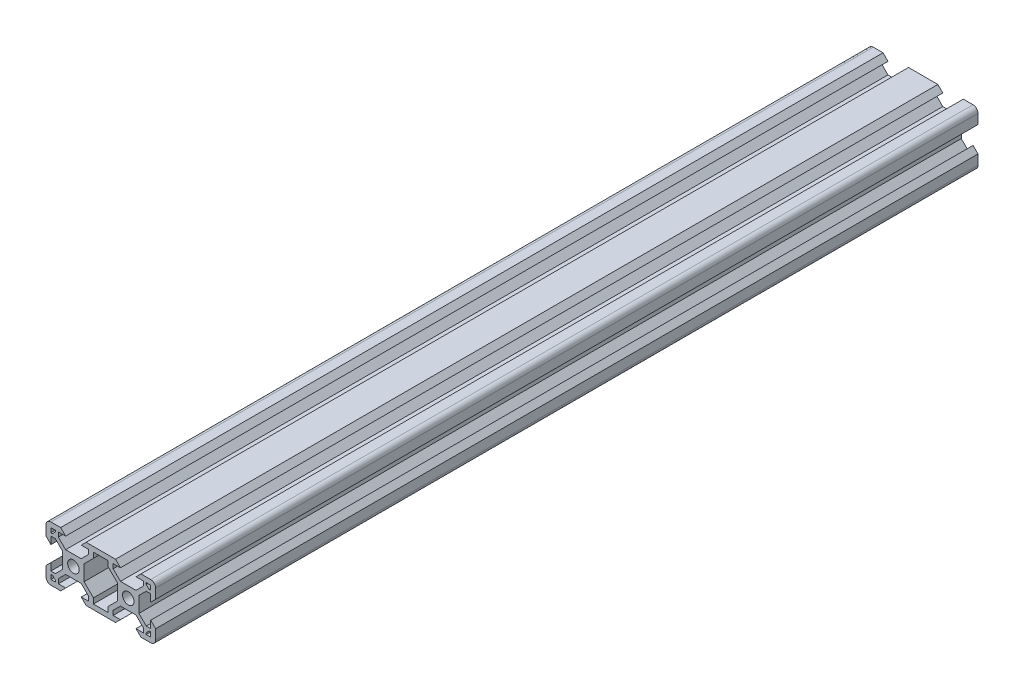
SolidWorks part; units mm, degrees
material "5052-H38, Barre (SS)"
ref_plane "Plan de face" through (0, 0, 0) normal (0, 0, 1) x (1, 0, 0)
ref_plane "Plan de dessus" through (0, 0, 0) normal (0, 1, 0) x (1, 0, 0)
ref_plane "Plan de droite" through (0, 0, 0) normal (1, 0, 0) x (0, 0, -1)
sketch "Esquisse1" plane through (0, 0, 0) normal (0, 0, 1) x (1, 0, 0)
  line L0 (0, 0) -> (0, 10) construction
  line L1 (0, 0) -> (-20, 0) construction
  line L2 (-10, 0) -> (-20, 10) construction
  line L3 (-10, 3.9007) -> (-12.84, 3.9007)
  line L4 (-12.84, 3.9007) -> (-15.4993, 6.56)
  line L5 (-15.4993, 6.56) -> (-15.4993, 8.2)
  line L6 (-15.4993, 8.2) -> (-12.84, 8.2)
  line L7 (-12.84, 8.2) -> (-14.64, 10)
  line L8 (-14.64, 10) -> (-18.2, 10)
  line L9 (-10, 0) -> (-10, 10) construction
  line L10 (-20, 4.64) -> (-20, 8.2)
  line L11 (-18.2, 2.84) -> (-20, 4.64)
  line L12 (-18.2, 5.4993) -> (-18.2, 2.84)
  line L13 (-16.56, 5.4993) -> (-18.2, 5.4993)
  line L14 (-13.9007, 2.84) -> (-16.56, 5.4993)
  line L15 (-13.9007, 0) -> (-13.9007, 2.84)
  line L16 (-10, -3.9007) -> (-12.84, -3.9007)
  line L17 (-12.84, -3.9007) -> (-15.4993, -6.56)
  line L18 (-15.4993, -6.56) -> (-15.4993, -8.2)
  line L19 (-15.4993, -8.2) -> (-12.84, -8.2)
  line L20 (-12.84, -8.2) -> (-14.64, -10)
  line L21 (-14.64, -10) -> (-18.2, -10)
  line L22 (-20, -4.64) -> (-20, -8.2)
  line L23 (-18.2, -2.84) -> (-20, -4.64)
  line L24 (-18.2, -5.4993) -> (-18.2, -2.84)
  line L25 (-16.56, -5.4993) -> (-18.2, -5.4993)
  line L26 (-13.9007, -2.84) -> (-16.56, -5.4993)
  line L27 (-13.9007, 0) -> (-13.9007, -2.84)
  line L28 (-10, 0) -> (0, 10) construction
  line L29 (-10, 3.9007) -> (-7.16, 3.9007)
  line L30 (-7.16, 3.9007) -> (-4.5007, 6.56)
  line L31 (-4.5007, 6.56) -> (-4.5007, 8.2)
  line L32 (-4.5007, 8.2) -> (-7.16, 8.2)
  line L33 (-7.16, 8.2) -> (-5.36, 10)
  line L34 (-7.16, -8.2) -> (-5.36, -10)
  line L35 (-4.5007, -8.2) -> (-7.16, -8.2)
  line L36 (-4.5007, -6.56) -> (-4.5007, -8.2)
  line L37 (-7.16, -3.9007) -> (-4.5007, -6.56)
  line L38 (-10, -3.9007) -> (-7.16, -3.9007)
  line L39 (-5.36, 10) -> (5.36, 10)
  line L40 (-5.36, -10) -> (5.36, -10)
  line L41 (-2.7, 8.2) -> (-2.7, 6.2393)
  line L42 (-2.7, 6.2393) -> (-6.0993, 2.84)
  line L43 (-2.7, 8.2) -> (2.7, 8.2)
  line L44 (-6.0993, 2.84) -> (-6.0993, -2.84)
  line L45 (-7.16, 3.9007) -> (-6.0993, 2.84) construction
  line L46 (-2.7, -8.2) -> (2.7, -8.2)
  line L47 (-2.7, -8.2) -> (-2.7, -6.2393)
  line L48 (-2.7, -6.2393) -> (-6.0993, -2.84)
  line L49 (-18.2, 8.2) -> (-18.2, 6.5693)
  line L50 (-18.2, 6.5693) -> (-17.63, 6.5693)
  line L51 (-17.63, 6.5693) -> (-16.5693, 7.63)
  line L52 (-16.5693, 7.63) -> (-16.5693, 8.2)
  line L53 (-16.5693, 8.2) -> (-18.2, 8.2)
  line L54 (-18.2, -6.5693) -> (-17.63, -6.5693)
  line L55 (-18.2, -8.2) -> (-18.2, -6.5693)
  line L56 (-16.5693, -8.2) -> (-18.2, -8.2)
  line L57 (-16.5693, -7.63) -> (-16.5693, -8.2)
  line L58 (-17.63, -6.5693) -> (-16.5693, -7.63)
  line L59 (18.2, 6.5693) -> (17.63, 6.5693)
  line L60 (18.2, 8.2) -> (18.2, 6.5693)
  line L61 (16.5693, 8.2) -> (18.2, 8.2)
  line L62 (16.5693, 7.63) -> (16.5693, 8.2)
  line L63 (17.63, 6.5693) -> (16.5693, 7.63)
  line L64 (18.2, -6.5693) -> (17.63, -6.5693)
  line L65 (18.2, -8.2) -> (18.2, -6.5693)
  line L66 (16.5693, -8.2) -> (18.2, -8.2)
  line L67 (16.5693, -7.63) -> (16.5693, -8.2)
  line L68 (17.63, -6.5693) -> (16.5693, -7.63)
  line L69 (2.7, 8.2) -> (2.7, 6.2393)
  line L70 (2.7, 6.2393) -> (6.0993, 2.84)
  line L71 (6.0993, 2.84) -> (6.0993, -2.84)
  line L72 (2.7, -6.2393) -> (6.0993, -2.84)
  line L73 (2.7, -8.2) -> (2.7, -6.2393)
  line L74 (7.16, -8.2) -> (5.36, -10)
  line L75 (4.5007, -8.2) -> (7.16, -8.2)
  line L76 (4.5007, -6.56) -> (4.5007, -8.2)
  line L77 (7.16, -3.9007) -> (4.5007, -6.56)
  line L78 (10, -3.9007) -> (7.16, -3.9007)
  line L79 (10, -3.9007) -> (12.84, -3.9007)
  line L80 (12.84, -3.9007) -> (15.4993, -6.56)
  line L81 (15.4993, -6.56) -> (15.4993, -8.2)
  line L82 (15.4993, -8.2) -> (12.84, -8.2)
  line L83 (12.84, -8.2) -> (14.64, -10)
  line L84 (14.64, -10) -> (18.2, -10)
  line L85 (20, -4.64) -> (20, -8.2)
  line L86 (18.2, -2.84) -> (20, -4.64)
  line L87 (18.2, -5.4993) -> (18.2, -2.84)
  line L88 (16.56, -5.4993) -> (18.2, -5.4993)
  line L89 (13.9007, -2.84) -> (16.56, -5.4993)
  line L90 (13.9007, 0) -> (13.9007, -2.84)
  line L91 (13.9007, 0) -> (13.9007, 2.84)
  line L92 (13.9007, 2.84) -> (16.56, 5.4993)
  line L93 (16.56, 5.4993) -> (18.2, 5.4993)
  line L94 (18.2, 5.4993) -> (18.2, 2.84)
  line L95 (18.2, 2.84) -> (20, 4.64)
  line L96 (20, 4.64) -> (20, 8.2)
  line L97 (14.64, 10) -> (18.2, 10)
  line L98 (12.84, 8.2) -> (14.64, 10)
  line L99 (15.4993, 8.2) -> (12.84, 8.2)
  line L100 (15.4993, 6.56) -> (15.4993, 8.2)
  line L101 (12.84, 3.9007) -> (15.4993, 6.56)
  line L102 (10, 3.9007) -> (12.84, 3.9007)
  line L103 (10, 3.9007) -> (7.16, 3.9007)
  line L104 (7.16, 3.9007) -> (4.5007, 6.56)
  line L105 (4.5007, 6.56) -> (4.5007, 8.2)
  line L106 (4.5007, 8.2) -> (7.16, 8.2)
  line L107 (7.16, 8.2) -> (5.36, 10)
  circle A0 centre (-10, 0) radius 2.1
  arc A1 (-18.2, 10) -> (-20, 8.2) centre (-18.2, 8.2) ccw
  arc A2 (-20, -8.2) -> (-18.2, -10) centre (-18.2, -8.2) ccw
  circle A3 centre (10, 0) radius 2.1
  arc A4 (20, -8.2) -> (18.2, -10) centre (18.2, -8.2) cw
  arc A5 (18.2, 10) -> (20, 8.2) centre (18.2, 8.2) cw
  point P57 (-6.0993, 0)
  point P61 (-17.0997, 7.0997)
  point P80 (0, 8.2)
  point P85 (0, -8.2)
  point P86 (0, -10)
  dimension "D3" = 4.2
  dimension "D2" = 20
  dimension "D4" = 5.68
  dimension "D5" = 1.5
  dimension "D6" = 1.8
  dimension "D7" = 1.64
  dimension "D11" = 5.4
  dimension "D12" = 1.07
  dimension "D8" = 2
  dimension "D9" = 2
  dimension "D10" = 2
extrude "Boss.-Extru.1" add sketch "Esquisse1" along normal mid plane 300
